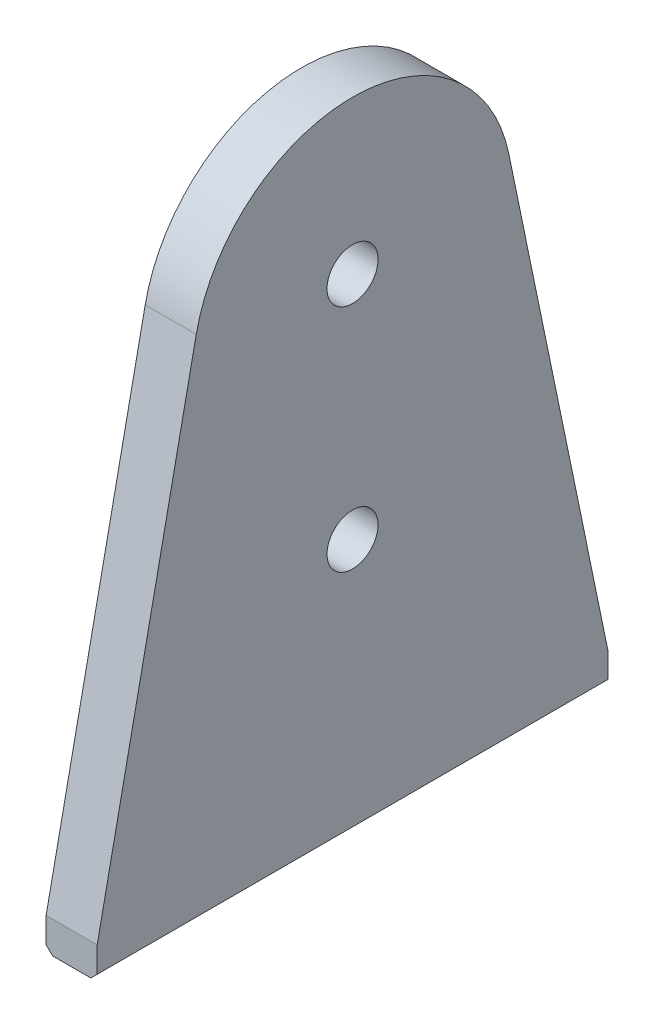
SolidWorks part; units mm, degrees
ref_plane "Front Plane" through (0, 0, 0) normal (0, 0, 1) x (1, 0, 0)
ref_plane "Top Plane" through (0, 0, 0) normal (0, 1, 0) x (1, 0, 0)
ref_plane "Right Plane" through (0, 0, 0) normal (1, 0, 0) x (0, 0, -1)
sketch "Sketch1" plane through (0, 0, 0) normal (1, 0, 0) x (0, 0, -1)
  line L0 (0, 40.0053) -> (0, 82.9629) construction
  line L1 (40, 0) -> (-40, 0)
  line L2 (-40, 0) -> (-40, 5)
  line L3 (-40, 5) -> (-24.4823, 80.0613)
  line L4 (40, 5) -> (24.4823, 80.0613)
  line L5 (40, 0) -> (40, 5)
  arc A0 (24.4823, 80.0613) -> (-24.4823, 80.0613) centre (0, 75) ccw
  circle A2 centre (0, 40) radius 4
  circle A3 centre (0, 76) radius 4
  point P16 (0, 0)
  dimension "D1" = 8
  dimension "D2" = 8
  dimension "D3" = 50
  dimension "D5" = 75
  dimension "D4" = 5
  dimension "D6" = 40
  dimension "D7" = 80
  dimension "D8" = 36
extrude "Boss-Extrude1" add sketch "Sketch1" along normal blind 8
chamfer "Chamfer1" distance 1 angle 45 2 edges at (8, 0, 0) (0, 0, 0)
